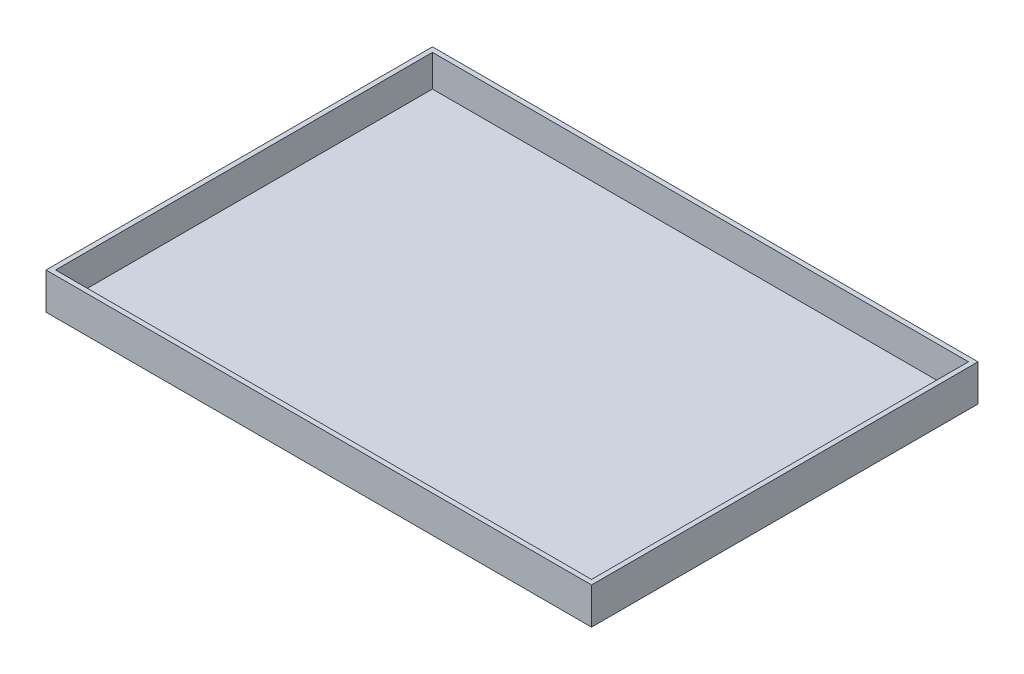
SolidWorks part; units mm, degrees
ref_plane "Front Plane" through (0, 0, 0) normal (0, 0, 1) x (1, 0, 0)
ref_plane "Top Plane" through (0, 0, 0) normal (0, 1, 0) x (1, 0, 0)
ref_plane "Right Plane" through (0, 0, 0) normal (1, 0, 0) x (0, 0, -1)
sketch "Sketch1" plane through (0, 0, 0) normal (0, 1, 0) x (1, 0, 0)
  line L1 (171.5, -121.5) -> (-171.5, -121.5)
  line L2 (171.5, -121.5) -> (171.5, 121.5)
  line L3 (171.5, 121.5) -> (-171.5, 121.5)
  line L4 (-171.5, -121.5) -> (-171.5, 121.5)
  line L5 (171.5, -121.5) -> (-171.5, 121.5) construction
  line L6 (171.5, 121.5) -> (-171.5, -121.5) construction
  line L7 (168.5, -118.5) -> (-168.5, -118.5)
  line L8 (168.5, -118.5) -> (168.5, 118.5)
  line L9 (168.5, 118.5) -> (-168.5, 118.5)
  line L10 (-168.5, -118.5) -> (-168.5, 118.5)
  line L11 (168.5, -118.5) -> (-168.5, 118.5) construction
  line L12 (168.5, 118.5) -> (-168.5, -118.5) construction
  point P0 (0, 0)
  point P6 (0, 0)
  dimension "D1" = 3
  dimension "D2" = 3
  dimension "D3" = 337
  dimension "D4" = 243
extrude "Boss-Extrude1" add sketch "Sketch1" along normal blind 23
sketch "Sketch2" plane through (0, 0, 0) normal (0, -1, 0) x (1, 0, 0)
  line L1 (-171.5, 121.5) -> (171.5, 121.5)
  line L2 (-171.5, 121.5) -> (-171.5, -121.5)
  line L3 (-171.5, -121.5) -> (171.5, -121.5)
  line L4 (171.5, 121.5) -> (171.5, -121.5)
extrude "Boss-Extrude2" add sketch "Sketch2" against normal blind 3
